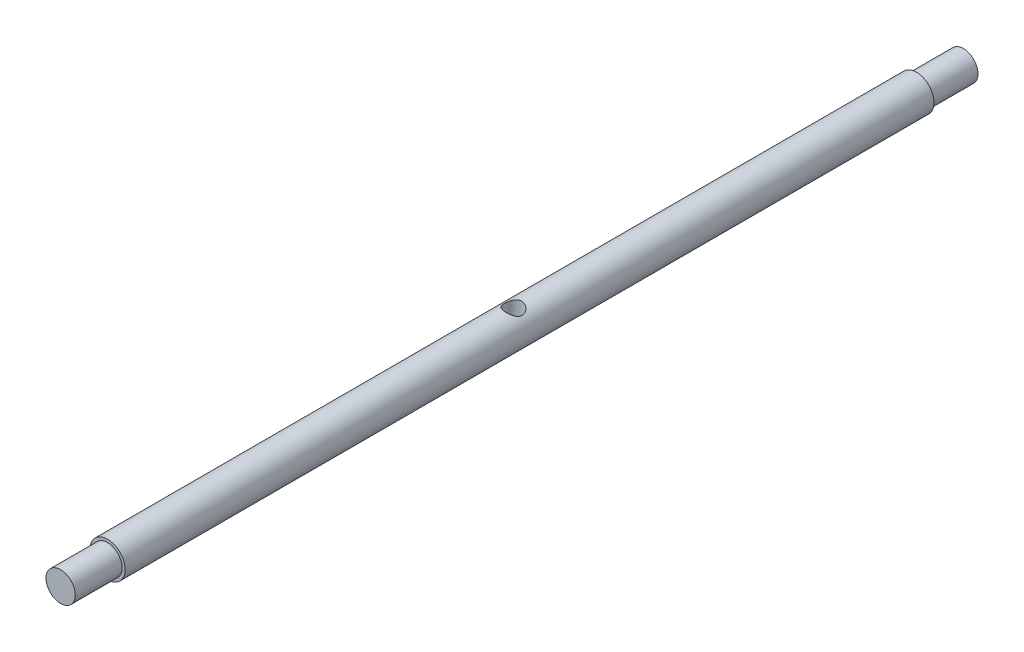
SolidWorks part; units mm, degrees
ref_plane "Front Plane" through (0, 0, 0) normal (0, 0, 1) x (1, 0, 0)
ref_plane "Top Plane" through (0, 0, 0) normal (0, 1, 0) x (1, 0, 0)
ref_plane "Right Plane" through (0, 0, 0) normal (1, 0, 0) x (0, 0, -1)
sketch "Sketch1" plane through (0, 0, 0) normal (0, 0, 1) x (1, 0, 0)
  circle A0 centre (0, 0) radius 3
  dimension "D1" = 6
extrude "Boss-Extrude1" add sketch "Sketch1" along normal blind 138
sketch "Sketch2" plane through (0, 0, 138) normal (0, 0, 1) x (1, 0, 0)
  circle A0 centre (0, 0) radius 2.5
  dimension "D1" = 5
extrude "Boss-Extrude2" add sketch "Sketch2" along normal blind 8
sketch "Sketch3" plane through (0, 0, 0) normal (0, 0, -1) x (-1, 0, 0)
  circle A0 centre (0, 0) radius 2.5
  dimension "D1" = 5
extrude "Boss-Extrude3" add sketch "Sketch3" along normal blind 8
sketch "Sketch4" plane through (0, 0, 0) normal (0, 1, 0) x (1, 0, 0)
  line L0 (3, -138) -> (-2.5, 0) construction
  circle A0 centre (0.25, -69) radius 1.5
  point P2 (0.25, -69)
  dimension "D1" = 3
extrude "Cut-Extrude1" cut sketch "Sketch4" against normal up to surface and the other way up to surface up to face at (3, 0, 138) other way up to face at (3, 0, 138)
